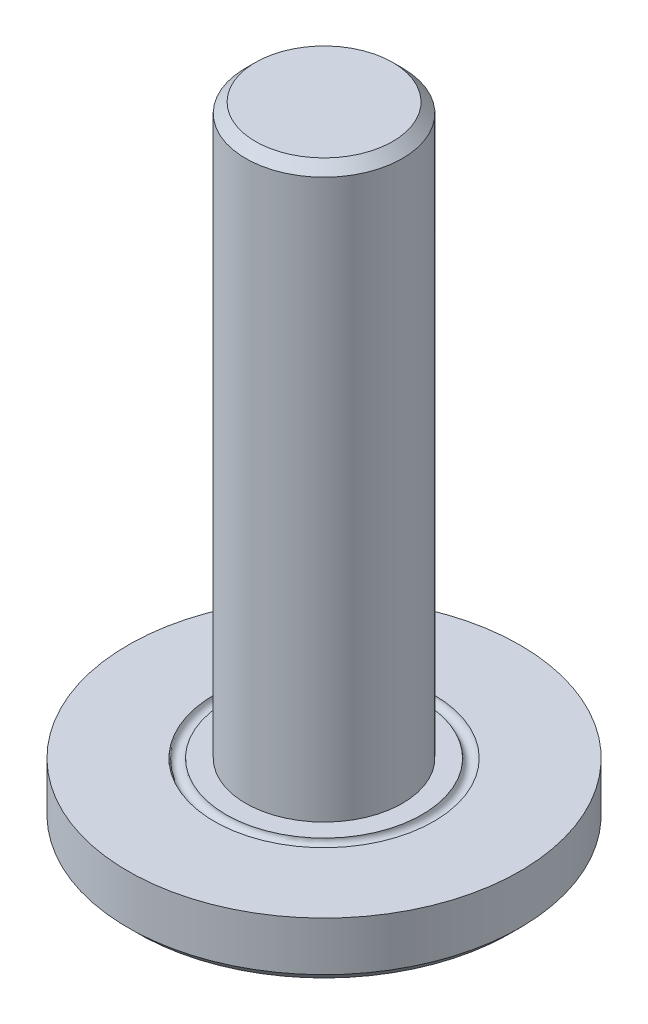
SolidWorks part; units mm, degrees
ref_plane "Plan1" through (0, 0, 0) normal (0, 0, 1) x (1, 0, 0)
ref_plane "Plan2" through (0, 0, 0) normal (0, 1, 0) x (1, 0, 0)
ref_plane "Plan3" through (0, 0, 0) normal (1, 0, 0) x (0, 0, -1)
ref_plane "Plan4" through (0, 0, 716.1319) normal (0, 0, -1) x (-1, 0, 0)
sketch "Esquisse1" plane through (0, 0, 716.1319) normal (0, 0, -1) x (-1, 0, 0)
  line L0 (-2169.9496, 588.7346) -> (-2160.4496, 588.7346)
  line L1 (-2160.4496, 588.7346) -> (-2160.4496, 620.7346)
  line L2 (-2160.4496, 620.7346) -> (-2163.9496, 620.7346)
  line L3 (-2163.9496, 620.7346) -> (-2164.4496, 620.2346)
  line L4 (-2164.4496, 620.2346) -> (-2164.4496, 605.5344)
  line L5 (-2164.4496, 605.5344) -> (-2164.4496, 591.7344)
  line L6 (-2164.4496, 591.7344) -> (-2165.4496, 591.7344)
  line L7 (-2166.0496, 591.7345) -> (-2170.4496, 591.7345)
  line L8 (-2170.4496, 591.7345) -> (-2170.4496, 589.2346)
  line L9 (-2170.4496, 589.2346) -> (-2169.9496, 588.7346)
  line L10 (-2160.4496, 588.7346) -> (-2160.4496, 615.3344) construction
  arc A1 (-2165.4496, 591.7344) -> (-2166.0496, 591.7345) centre (-2165.7496, 591.7344) cw
  dimension "D4" = 0.3
  dimension "D8" = 10
  dimension "D2" = 2.9999
  dimension "D3" = 32
  dimension "D7" = 4
  dimension "D9" = 0.5
  dimension "D10" = 45
  dimension "D11" = 0.5
  dimension "D12" = 45
revolve "Base-Révolution" add sketch "Esquisse1" angle 360 about L10
